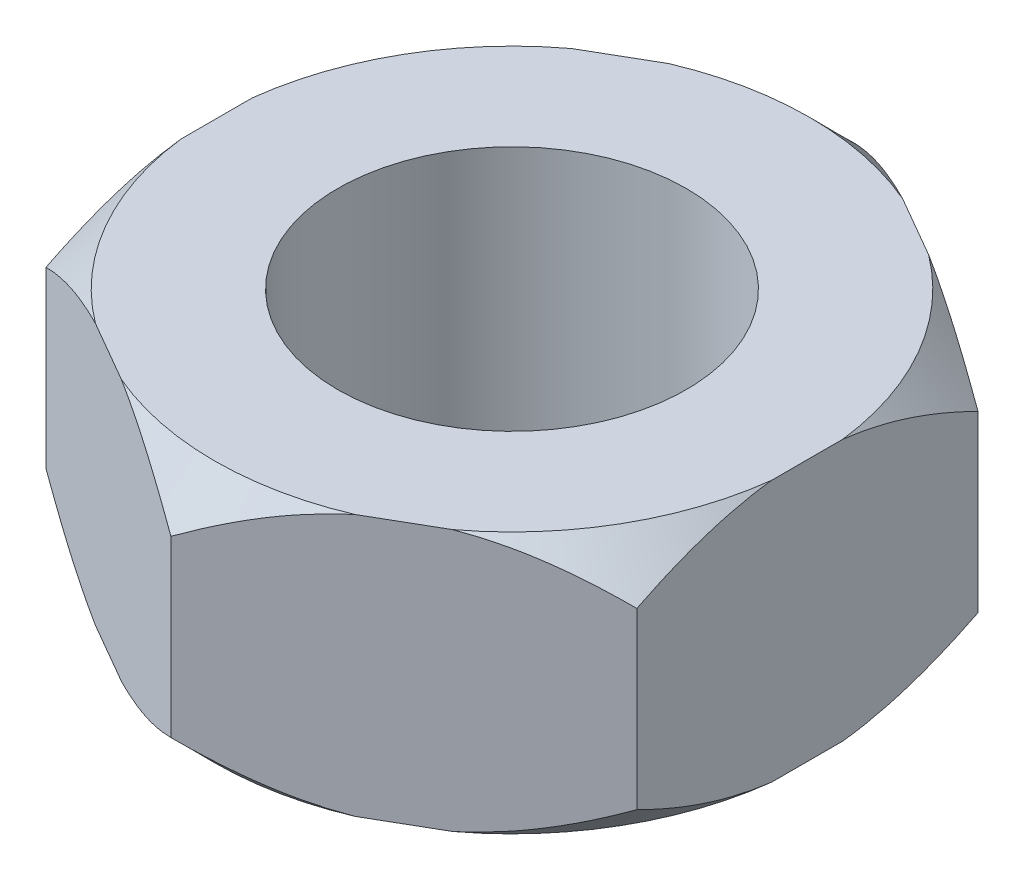
SolidWorks part; units mm, degrees
ref_plane "前视基准面" through (0, 0, 0) normal (0, 0, 1) x (1, 0, 0)
ref_plane "上视基准面" through (0, 0, 0) normal (0, 1, 0) x (1, 0, 0)
ref_plane "右视基准面" through (0, 0, 0) normal (1, 0, 0) x (0, 0, -1)
sketch "草图1" plane through (0, 0, 0) normal (0, 1, 0) x (1, 0, 0)
  line L1 (0, 3.9144) -> (-3.39, 1.9572)
  line L2 (-3.39, 1.9572) -> (-3.39, -1.9572)
  line L3 (-3.39, -1.9572) -> (0, -3.9144)
  line L4 (0, -3.9144) -> (3.39, -1.9572)
  line L5 (3.39, -1.9572) -> (3.39, 1.9572)
  line L6 (3.39, 1.9572) -> (0, 3.9144)
  circle A0 centre (0, 0) radius 3.39 construction
  circle A1 centre (0, 0) radius 2
  dimension "D2" = 4
  dimension "D1" = 6.78
extrude "凸台-拉伸1" add sketch "草图1" along normal blind 3
ref_plane "基准面1" through (0, 2.5, 0) normal (0, 1, 0) x (1, 0, 0)
ref_plane "基准面2" through (0, 0, 0) normal (0.5, 0, -0.866) x (-0.866, 0, -0.5)
sketch "草图12" plane through (0, 0, 0) normal (0.5, 0, -0.866) x (-0.866, 0, -0.5)
  line L0 (-3.9144, 3) -> (-3.9144, 2.5)
  line L1 (-3.9144, 3) -> (-1.9572, 3) construction
  line L2 (-3.4144, 3) -> (-3.9144, 2.5)
  line L4 (-3.4144, 3) -> (-3.9144, 3)
  line L5 (0, 3) -> (0, 4.1093)
  dimension "D1" = 0.5
  dimension "D2" = 0
  dimension "D3" = 0.5
revolve "切除-旋转1" cut sketch "草图12" angle 360 about L5
ref_plane "基准面3" through (0, 1.5, 0) normal (0, 1, 0) x (1, 0, 0)
mirror "镜向1" about plane through (0, 1.5, 0) normal (0, 1, 0) of "切除-旋转1"
